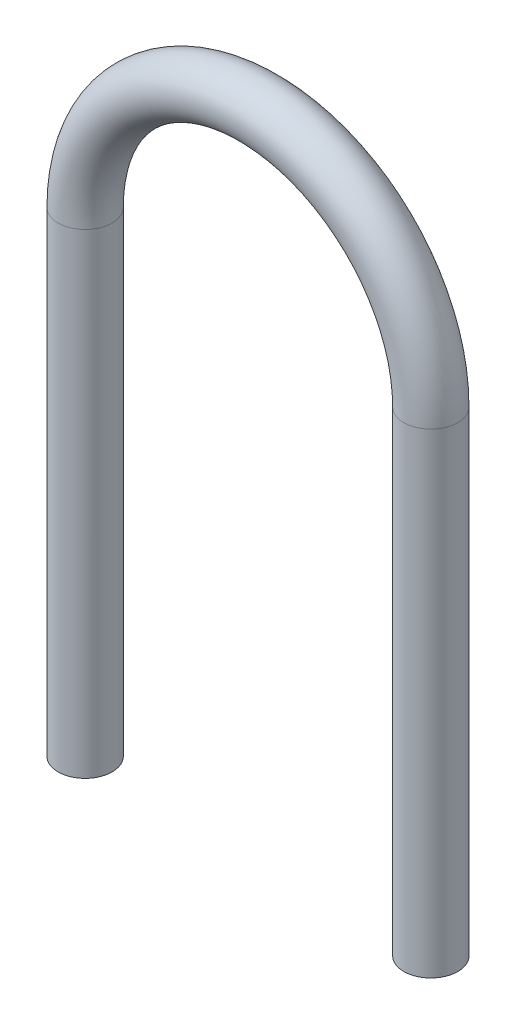
SolidWorks part; units mm, degrees
ref_plane "Plan de face" through (0, 0, 0) normal (0, 0, 1) x (1, 0, 0)
ref_plane "Plan de dessus" through (0, 0, 0) normal (0, 1, 0) x (1, 0, 0)
ref_plane "Plan de droite" through (0, 0, 0) normal (1, 0, 0) x (0, 0, -1)
sketch "Esquisse1" plane through (0, 0, 0) normal (0, 0, 1) x (1, 0, 0)
  line L0 (-25.4, 0) -> (-25.4, -69.85)
  line L1 (25.4, 0) -> (25.4, -69.85)
  arc A0 (25.4, 0) -> (-25.4, 0) centre (0, 0) ccw
  dimension "D1" = 50.8
  dimension "D2" = 95.25
ref_plane "Plan1" through (0, -69.85, 0) normal (0, 1, 0) x (-1, 0, 0)
sketch "Esquisse4" plane through (0, -69.85, 0) normal (0, 1, 0) x (-1, 0, 0)
  circle A0 centre (-25.4, 0) radius 3.9688
  dimension "D1" = 7.9375
sweep "Balayage1" add profiles "Esquisse4" path "Esquisse1"
